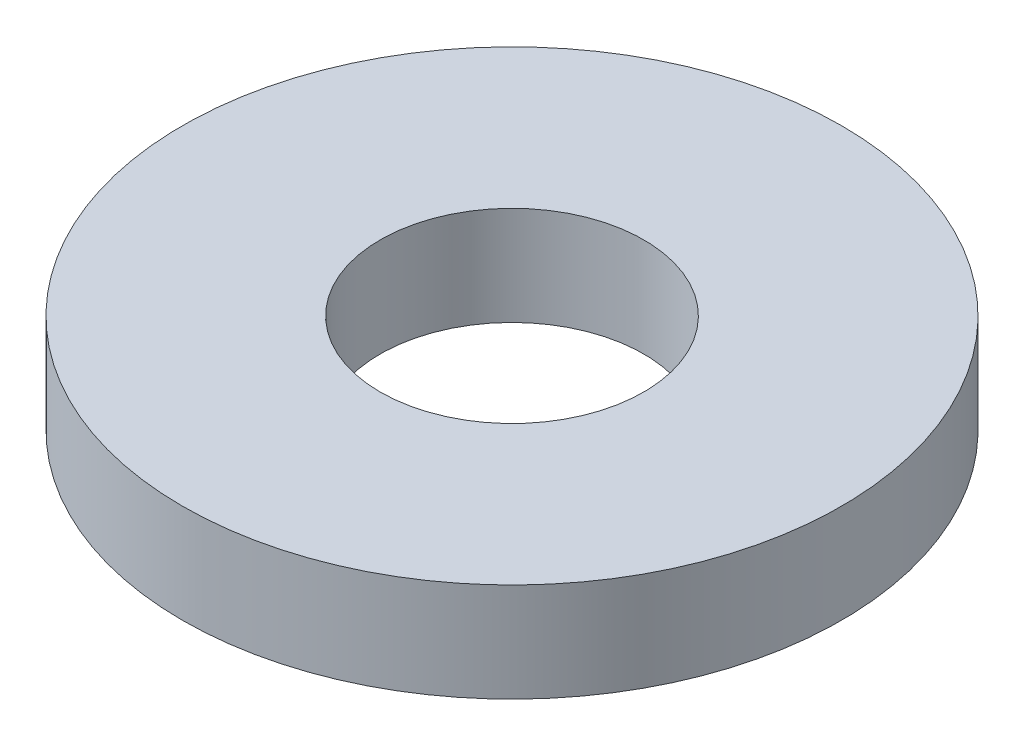
SolidWorks part; units mm, degrees
material "Oak"
ref_plane "Front Plane" through (0, 0, 0) normal (0, 0, 1) x (1, 0, 0)
ref_plane "Top Plane" through (0, 0, 0) normal (0, 1, 0) x (1, 0, 0)
ref_plane "Right Plane" through (0, 0, 0) normal (1, 0, 0) x (0, 0, -1)
sketch "Sketch1" plane through (0, 0, 0) normal (0, 1, 0) x (1, 0, 0)
  circle A0 centre (0, 0) radius 10
  circle A1 centre (0, 0) radius 4
  dimension "D1" = 20
  dimension "D2" = 8
extrude "Boss-Extrude1" add sketch "Sketch1" along normal blind 3
